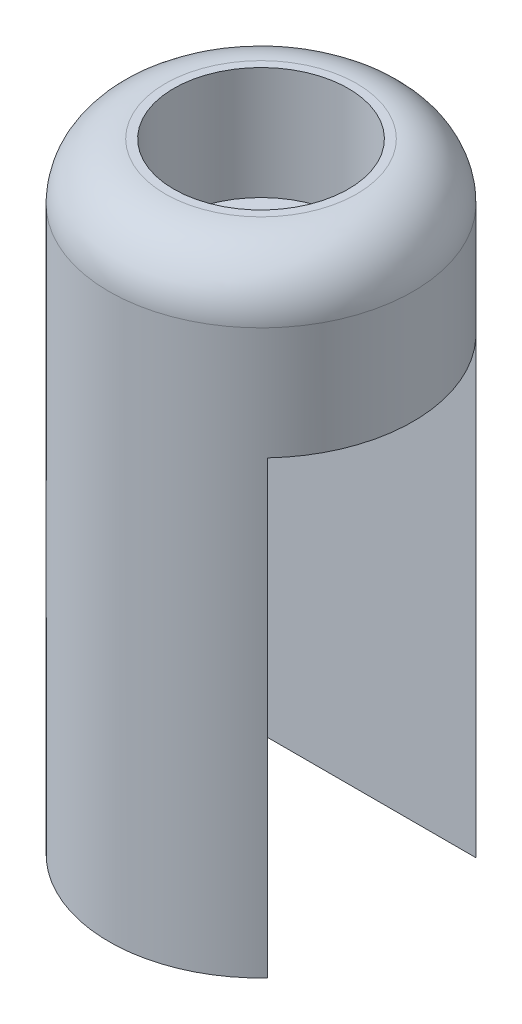
SolidWorks part; units mm, degrees
ref_plane "Front Plane" through (0, 0, 0) normal (0, 0, 1) x (1, 0, 0)
ref_plane "Top Plane" through (0, 0, 0) normal (0, 1, 0) x (1, 0, 0)
ref_plane "Right Plane" through (0, 0, 0) normal (1, 0, 0) x (0, 0, -1)
sketch "Sketch1" plane through (0, 0, 0) normal (0, 1, 0) x (1, 0, 0)
  circle A0 centre (0, 0) radius 2.7
extrude "Boss-Extrude1" add sketch "Sketch1" along normal blind 11
sketch "Sketch2" plane through (0, 0, 0) normal (0, -1, 0) x (1, 0, 0)
  line L2 (1.9666, 1.85) -> (-1.9666, 1.85)
  line L3 (1.9666, -1.85) -> (-1.9666, -1.85)
  arc A1 (-1.9666, 1.85) -> (-1.9666, -1.85) centre (0, 0) ccw
  arc A2 (1.9666, -1.85) -> (1.9666, 1.85) centre (0, 0) ccw
extrude "Cut-Extrude1" cut sketch "Sketch2" against normal blind 8
sketch "Sketch3" plane through (0, 11, 0) normal (0, 1, 0) x (1, 0, 0)
  circle A0 centre (0, 0) radius 1.55
  dimension "D1" = 3.1
extrude "Cut-Extrude2" cut sketch "Sketch3" against normal blind 2
fillet "Fillet1" radius 1 1 edges at (0, 11, 2.7)
